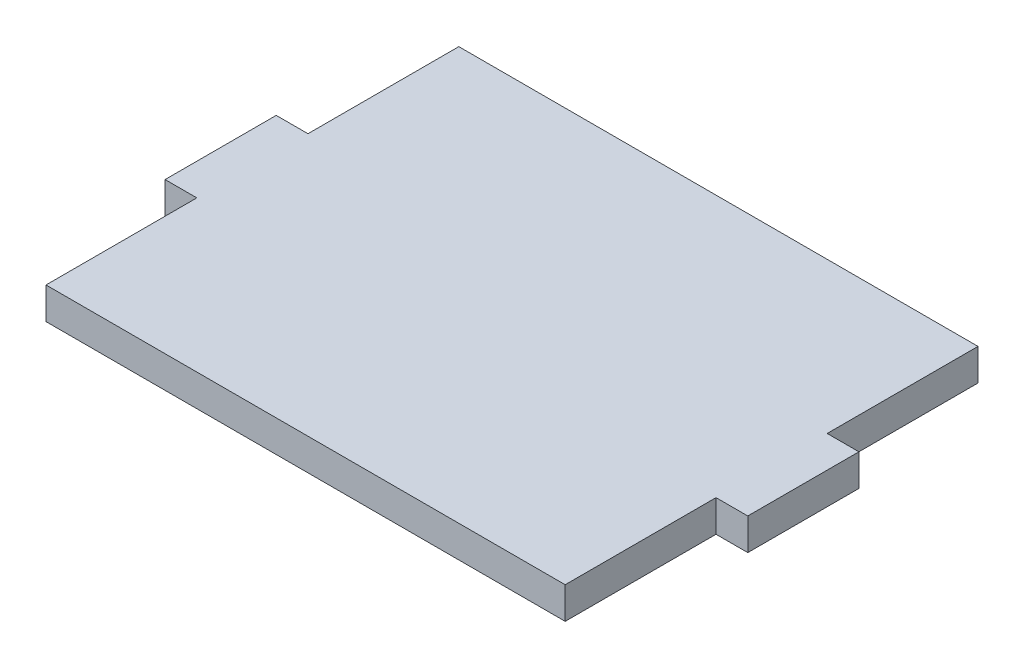
SolidWorks part; units mm, degrees
ref_plane "Front Plane" through (0, 0, 0) normal (0, 0, 1) x (1, 0, 0)
ref_plane "Top Plane" through (0, 0, 0) normal (0, 1, 0) x (1, 0, 0)
ref_plane "Right Plane" through (0, 0, 0) normal (1, 0, 0) x (0, 0, -1)
sketch "Sketch1" plane through (0, 0, 0) normal (0, 1, 0) x (1, 0, 0)
  line L1 (-16.35, 13) -> (16.35, 13)
  line L2 (-16.35, 13) -> (-16.35, -13)
  line L3 (-16.35, -13) -> (16.35, -13)
  line L4 (16.35, 13) -> (16.35, -13)
  line L5 (-16.35, 13) -> (16.35, -13) construction
  line L6 (-16.35, -13) -> (16.35, 13) construction
  line L7 (16.35, -3.5) -> (18.35, -3.5)
  line L8 (16.35, -3.5) -> (16.35, 3.5)
  line L9 (16.35, 3.5) -> (18.35, 3.5)
  line L10 (18.35, -3.5) -> (18.35, 3.5)
  line L11 (-16.35, 3.5) -> (-18.35, 3.5)
  line L12 (-16.35, 3.5) -> (-16.35, -3.5)
  line L13 (-16.35, -3.5) -> (-18.35, -3.5)
  line L14 (-18.35, 3.5) -> (-18.35, -3.5)
  point P0 (0, 0)
  dimension "D1" = 26
  dimension "D2" = 32.7
  dimension "D3" = 2
  dimension "D4" = 2
  dimension "D5" = 7
  dimension "D6" = 7
  dimension "D7" = 9.5
  dimension "D8" = 9.5
extrude "Boss-Extrude1" add sketch "Sketch1" along normal blind 2 contours L4 L1 L2 L3 | L11 L14 L13 L2 | L7 L10 L9 L4
